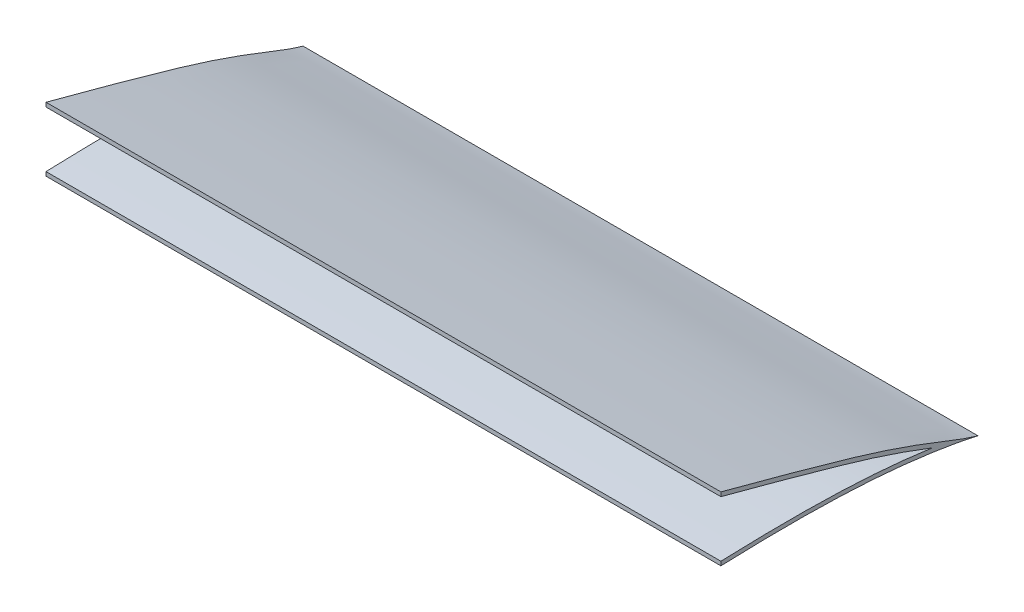
SolidWorks part; units mm, degrees
material "Balsa"
ref_plane "Front" through (0, 0, 0) normal (0, 0, 1) x (1, 0, 0)
ref_plane "Top" through (0, 0, 0) normal (0, 1, 0) x (1, 0, 0)
ref_plane "Right" through (0, 0, 0) normal (1, 0, 0) x (0, 0, -1)
sketch "Sketch1" plane through (0, 0, 0) normal (1, 0, 0) x (0, 0, -1)
  line L0 (700.5511, 3.5862) -> (700.5511, 1.945) construction
  line L1 (700.5511, 3.5862) -> (700.5511, -21.7251)
  spline S0 degree 3 poles (-4981.8342, -396.5609) (91.8087, 63.6859) (-5.3281, 25.3313) (0.5702, -4.3968) (2.5361, -10.6164) (7.9982, -20.5501) (16.1137, -34.185) (25.7513, -48.9002) (36.932, -62.9388) (49.3364, -75.9186) (65.2269, -85.625) (84.4528, -91.7174) (106.8521, -96.1515) (132.5109, -98.5722) (161.1944, -99.0924) (192.7613, -97.7042) (227.0382, -94.5118) (263.8348, -89.6638) (302.9215, -83.3884) (344.0178, -75.9778) (386.7768, -67.7807) (430.7746, -59.2023) (475.4963, -50.6638) (520.3353, -42.6036) (564.5889, -35.4228) (607.4709, -29.4733) (648.1275, -25.0145) (685.6676, -22.1862) (719.1968, -21.0048) (747.8303, -21.2786) (770.6884, -22.8547) (787.0914, -25.0735) (876.8677, -41.1472) (945.9809, -128.2669) (2071.1001, 4801.8764) knots -0.096815 -0.096815 -0.096815 -0.096815 0.001821 0.004613 0.009135 0.024676 0.044153 0.064937 0.086321 0.107138 0.1276 0.150893 0.177565 0.207668 0.241222 0.278203 0.318526 0.362031 0.408465 0.457479 0.508614 0.561296 0.614835 0.668438 0.721214 0.772202 0.820393 0.864766 0.904324 0.938132 0.965242 0.98469 0.99621 1.28526 1.28526 1.28526 1.28526 only from (0, 0) to (802.1511, -28.0117) construction
  spline S1 degree 3 poles (-595.9868, -4824.44) (948.5227, 15.9159) (856.0345, -49.5998) (789.3572, -23.4586) (777.0615, -18.6436) (760.5817, -13.0401) (739.9968, -7.1233) (715.5772, -0.3798) (687.647, 7.013) (656.6835, 14.9584) (623.1589, 23.2583) (587.5492, 31.6944) (550.3192, 40.0262) (511.9148, 48.0016) (472.7617, 55.3745) (433.2622, 61.9128) (393.7959, 67.4048) (354.7199, 71.6552) (316.357, 74.5357) (278.9313, 75.7536) (242.6994, 75.3938) (207.8706, 73.5467) (174.7468, 70.259) (143.6014, 65.7682) (114.7621, 60.1875) (88.5345, 53.6285) (65.199, 46.2382) (45.0006, 38.1339) (28.1586, 29.5092) (14.871, 20.5578) (6.1442, 12.3133) (1.9481, 6.1765) (0.6391, 3.0841) (0.217, 1.668) (-3.0517, -15.0089) (59.3046, -37.645) (-4977.732, 428.207) knots -0.226708 -0.226708 -0.226708 -0.226708 0.003802 0.014472 0.030564 0.051299 0.077028 0.107574 0.142399 0.180921 0.222525 0.266591 0.312515 0.35971 0.407632 0.455773 0.503669 0.550901 0.597096 0.641976 0.685512 0.727353 0.767354 0.805169 0.840471 0.872937 0.902335 0.928425 0.951113 0.970253 0.985871 0.993982 0.996753 0.997907 0.999293 1.057589 1.057589 1.057589 1.057589 only from (802.1511, -28.0117) to (0, 0) construction
  spline S2 degree 3 poles (0, 0) (0.0175, -0.519) (0.0617, -1.8338) (0.5702, -4.3968) (2.5361, -10.6164) (7.9982, -20.5501) (16.1137, -34.185) (25.7513, -48.9002) (36.932, -62.9388) (49.3364, -75.9186) (65.2269, -85.625) (84.4528, -91.7174) (106.8521, -96.1515) (132.5109, -98.5722) (161.1944, -99.0924) (192.7613, -97.7042) (227.0382, -94.5118) (263.8348, -89.6638) (302.9215, -83.3884) (344.0178, -75.9778) (386.7768, -67.7807) (430.7746, -59.2023) (475.4963, -50.6638) (520.3353, -42.6036) (564.5889, -35.4228) (607.4709, -29.4733) (648.1275, -25.0145) (685.6676, -22.1862) (719.1968, -21.0048) (747.8303, -21.2786) (770.6884, -22.8547) (787.0914, -25.0735) (796.8423, -26.8193) (801.0977, -27.7751) (802.1511, -28.0117) knots 0 0 0 0 0.001821 0.004613 0.009135 0.024676 0.044153 0.064937 0.086321 0.107138 0.1276 0.150893 0.177565 0.207668 0.241222 0.278203 0.318526 0.362031 0.408465 0.457479 0.508614 0.561296 0.614835 0.668438 0.721214 0.772202 0.820393 0.864766 0.904324 0.938132 0.965242 0.98469 0.99621 1 1 1 1
  spline S3 degree 3 poles (802.1511, -28.0117) (801.1372, -27.7105) (797.2784, -26.5642) (789.3572, -23.4586) (777.0615, -18.6436) (760.5817, -13.0401) (739.9968, -7.1233) (715.5772, -0.3798) (687.647, 7.013) (656.6835, 14.9584) (623.1589, 23.2583) (587.5492, 31.6944) (550.3192, 40.0262) (511.9148, 48.0016) (472.7617, 55.3745) (433.2622, 61.9128) (393.7959, 67.4048) (354.7199, 71.6552) (316.357, 74.5357) (278.9313, 75.7536) (242.6994, 75.3938) (207.8706, 73.5467) (174.7468, 70.259) (143.6014, 65.7682) (114.7621, 60.1875) (88.5345, 53.6285) (65.199, 46.2382) (45.0006, 38.1339) (28.1586, 29.5092) (14.871, 20.5578) (6.1442, 12.3133) (1.9481, 6.1765) (0.6391, 3.0841) (0.217, 1.668) (0.0426, 0.7778) (0.0107, 0.1963) (0, 0) knots 0 0 0 0 0.003802 0.014472 0.030564 0.051299 0.077028 0.107574 0.142399 0.180921 0.222525 0.266591 0.312515 0.35971 0.407632 0.455773 0.503669 0.550901 0.597096 0.641976 0.685512 0.727353 0.767354 0.805169 0.840471 0.872937 0.902335 0.928425 0.951113 0.970253 0.985871 0.993982 0.996753 0.997907 0.999293 1 1 1 1
  spline S4 degree 1 poles (1.589, -0.0169) (784.1065, -23.1184) knots 0 0 1 1 construction
  spline S5 degree 1 poles (784.1065, -23.1184) (1.589, -0.0169) knots 0 0 1 1 construction
  spline S6 degree 3 poles (1.589, -0.0169) (1.5978, -0.2781) (1.617, -0.8171) (1.6706, -1.5251) (1.7727, -2.2395) (1.9645, -3.217) (2.2822, -4.4731) (2.892, -6.4557) (3.825, -8.9127) (5.5748, -12.7649) (8.1549, -17.4947) (12.5101, -25.0363) (18.1123, -34.2943) (25.2301, -45.181) (31.6891, -53.8227) (37.2128, -60.4726) (42.9501, -66.9629) (50.6018, -74.4394) (61.3489, -81.5128) (73.1594, -86.5673) (85.641, -90.1112) (98.3223, -92.8576) (115.4237, -95.4885) (137.057, -97.1574) (163.0971, -97.3914) (189.1354, -96.2564) (215.1195, -94.0861) (241.0338, -91.1098) (275.4921, -86.3076) (318.4041, -79.1225) (369.7356, -69.4844) (421.0135, -59.4768) (472.335, -49.6151) (523.7845, -40.3589) (575.4257, -32.1357) (627.3021, -25.4119) (670.7418, -21.5032) (705.604, -19.8163) (731.789, -19.4122) (758.0003, -20.1502) (775.4469, -21.8673) (784.1065, -23.1184) knots 0.000082 0.000082 0.000082 0.000082 0.001038 0.001993 0.002948 0.003903 0.005814 0.007724 0.011545 0.015366 0.023009 0.030651 0.045935 0.061219 0.076503 0.084145 0.091787 0.107071 0.122355 0.137639 0.152923 0.168208 0.183492 0.21406 0.244628 0.275196 0.305765 0.336333 0.366901 0.428038 0.489174 0.55031 0.611447 0.672583 0.73372 0.794856 0.855993 0.886561 0.917129 0.947697 0.978266 0.978266 0.978266 0.978266
  spline S7 degree 3 poles (784.1065, -23.1184) (780.1603, -21.5942) (772.229, -18.642) (760.1745, -14.6722) (747.9911, -11.0613) (731.6457, -6.456) (711.1768, -0.8453) (678.3297, 7.8115) (637.1713, 18.2575) (587.6183, 30.1162) (537.8777, 41.1375) (487.9189, 51.0912) (437.7208, 59.724) (387.2787, 66.7289) (345.0506, 70.936) (311.1879, 73.0641) (277.2796, 74.2092) (243.3427, 73.88) (209.4764, 71.9586) (184.1438, 69.6475) (158.905, 66.4678) (133.8072, 62.3586) (108.9155, 57.1874) (88.425, 51.8354) (72.2738, 46.7811) (60.3184, 42.5401) (48.5771, 37.7737) (37.1197, 32.3878) (27.9272, 27.2538) (20.9064, 22.6554) (15.8717, 18.9075) (11.1186, 14.8241) (7.5582, 11.0807) (5.0251, 7.8349) (3.3892, 5.2955) (2.3111, 3.0614) (1.8056, 1.4859) (1.654, 0.7258) (1.6104, 0.3499) (1.5955, 0.1003) (1.589, -0.0169) knots 0.0223 0.0223 0.0223 0.0223 0.037575 0.05285 0.068125 0.083401 0.113951 0.144502 0.205603 0.266703 0.327804 0.388905 0.450006 0.511107 0.572208 0.602759 0.633309 0.69441 0.724961 0.755511 0.786062 0.816612 0.847162 0.877713 0.892988 0.908263 0.923539 0.938814 0.954089 0.961727 0.969364 0.977002 0.98464 0.988458 0.992277 0.996096 0.998005 0.99896 0.999438 0.999915 0.999915 0.999915 0.999915
  dimension "D1" = 1.5875
extrude "Boss-Extrude1" add sketch "Sketch1" along normal up to vertex (266.7 mm away) contours S7 S6 L1 S2 S3
